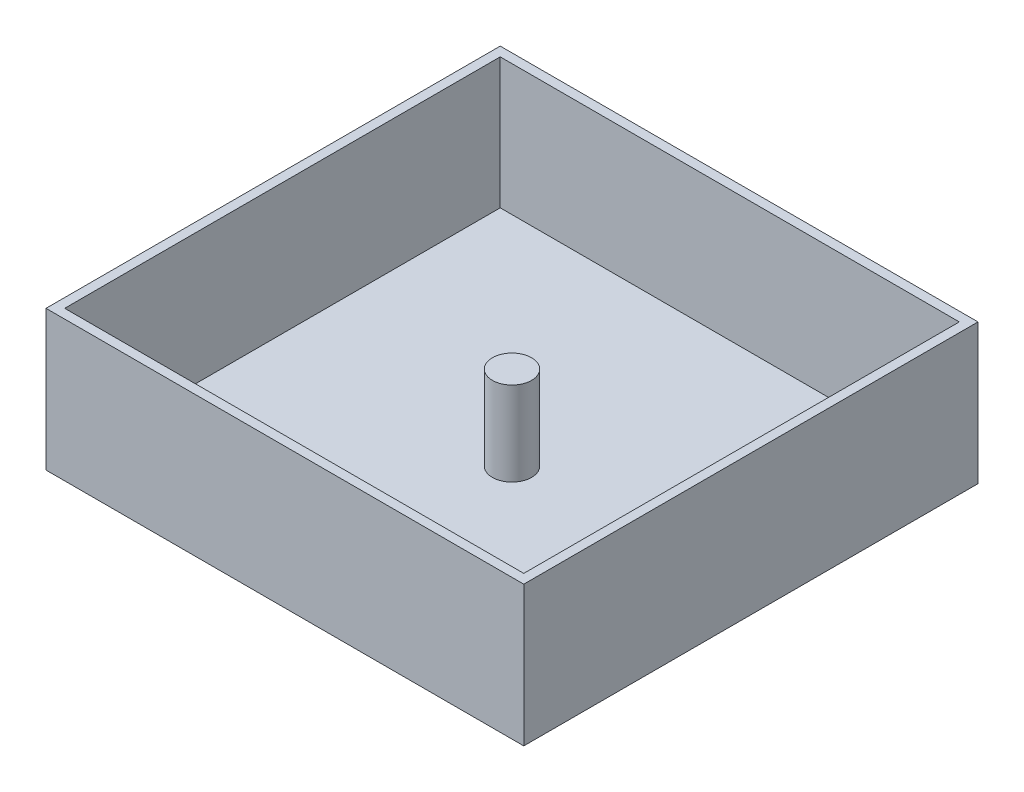
SolidWorks part; units mm, degrees
material "Alloy Steel"
ref_plane "Front Plane" through (0, 0, 0) normal (0, 0, 1) x (1, 0, 0)
ref_plane "Top Plane" through (0, 0, 0) normal (0, 1, 0) x (1, 0, 0)
ref_plane "Right Plane" through (0, 0, 0) normal (1, 0, 0) x (0, 0, -1)
sketch "Sketch1" plane through (0, 0, 0) normal (0, 1, 0) x (1, 0, 0)
  line L1 (-255.765, 243.16) -> (255.765, 243.16)
  line L2 (-255.765, 243.16) -> (-255.765, -243.16)
  line L3 (-255.765, -243.16) -> (255.765, -243.16)
  line L4 (255.765, 243.16) -> (255.765, -243.16)
  line L5 (-255.765, 243.16) -> (255.765, -243.16) construction
  line L6 (-255.765, -243.16) -> (255.765, 243.16) construction
  point P0 (0, 0)
  dimension "D1" = 486.32
  dimension "D2" = 511.53
extrude "Boss-Extrude1" add sketch "Sketch1" along normal blind 150
shell "Shell1" thickness 10
sketch "Sketch2" plane through (0, 10, 0) normal (0, 1, 0) x (1, 0, 0)
  circle A0 centre (0, 0) radius 21
  dimension "D1" = 42
extrude "Boss-Extrude2" add sketch "Sketch2" along normal blind 90
scale "Scale1" scale about origin uniform scaling yes scale factor 0.1
scale "Scale2" bodies to scale 103 scale about origin uniform scaling yes scale factor 3
